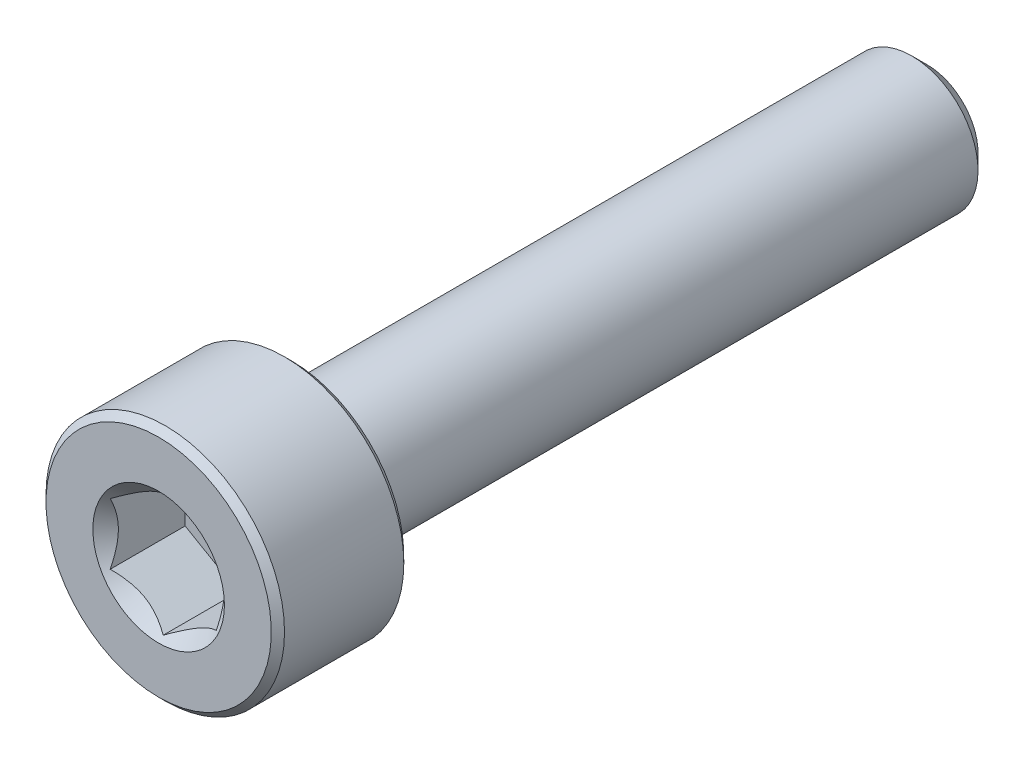
SolidWorks part; units mm, degrees
ref_plane "Front Plane" through (0, 0, 0) normal (0, 0, 1) x (1, 0, 0)
ref_plane "Top Plane" through (0, 0, 0) normal (0, 1, 0) x (1, 0, 0)
ref_plane "Right Plane" through (0, 0, 0) normal (1, 0, 0) x (0, 0, -1)
sketch "Sketch1" plane through (0, 0, 0) normal (1, 0, 0) x (0, 0, -1)
  line L0 (-7.25, 0) -> (7.25, 0) construction
  line L1 (7.25, 0) -> (7.25, 0.9577) construction
  line L2 (7.25, 0.9577) -> (6.9577, 1.25) construction
  line L3 (6.9577, 1.25) -> (6.9125, 1.25) construction
  line L4 (6.9125, 1.25) -> (-4.75, 1.25) construction
  line L5 (-4.75, 1.25) -> (-4.75, 2.25) construction
  line L6 (-4.75, 2.25) -> (-7.25, 2.25) construction
  line L7 (-7.25, 2.25) -> (-7.25, 0) construction
  line L8 (7.25, 0.9577) -> (7.25, 1.25) construction
  line L9 (7.2219, 1.2987) -> (7.4469, 0.909) construction
  line L10 (7.4469, 0.909) -> (7.6719, 1.2987) construction
  line L11 (7.6719, 1.2987) -> (7.2219, 1.2987) construction
  line L12 (7.4469, 1.2987) -> (7.4469, 1.25) construction
  line L13 (7.4469, 0.909) -> (7.4469, 0.9577) construction
  line L14 (7.4187, 0.9577) -> (7.475, 0.9577) construction
  line L15 (7.25, 1.25) -> (7.6438, 1.25) construction
  line L16 (7.2359, 1.2744) -> (7.6578, 1.2744) construction
  line L17 (7.25, 0) -> (7.25, -1.25) construction
  line L18 (-4.875, 2.25) -> (-4.75, 2.125) construction
  line L19 (-7.125, 2.25) -> (-7.25, 2.125) construction
  line L20 (-4.75, 1.25) -> (-4.75, 0) construction
  line L21 (-4.75, 0.625) -> (-0.75, 0.625) construction
  line L22 (-0.75, 0.625) -> (3.25, 0.625) construction
  line L23 (3.25, 0.625) -> (7.25, 0.625) construction
  line L24 (-0.75, 0.625) -> (-0.75, 1.25) construction
  line L25 (-0.75, 1.25) -> (-0.75, 2.25) construction
  line L26 (3.25, 0.625) -> (3.25, 2.25) construction
  point P0 (-7.25, 1)
  point P3 (6.125, 1.25)
  point P4 (0, 0)
  point P18 (3.25, 1.25)
  point P22 (7.4469, 0.9577)
  point P24 (6.9125, 1.25)
  point P25 (7.4469, 1.25)
  point P28 (7.4469, 1.2744)
  point P29 (6.125, -1.25)
  point P30 (-0.75, 1.25)
  point P31 (-6, 2.25)
  point P37 (-5.1875, 2.25)
  point P38 (-7.0625, 2.25)
  point P45 (-0.75, 0.625)
  point P46 (3.25, 0.625)
  dimension "D2" = 0.0563
  dimension "D7" = 0.125
  dimension "D8" = 0.125
  dimension "D9" = 0.125
  dimension "D10" = 0.0625
  dimension "D11" = 0.3125
  dimension "Drive Size" = 2
  dimension "Head Diameter" = 4.5
  dimension "Head Height" = 2.5
  dimension "Thread Pitch" = 0.45
  dimension "Thread Dia" = 2.5
  dimension "Length" = 12
  dimension "D12" = 0.3375
  dimension "D4" = 1.125
  dimension "D3" = 45
sketch "Sketch2" plane through (0, 0, 0) normal (1, 0, 0) x (0, 0, -1)
  line L0 (-7.25, 0) -> (-7.25, 2.125)
  line L1 (-7.125, 2.25) -> (-4.875, 2.25)
  line L2 (-4.75, 2.125) -> (-4.75, 1.375)
  line L4 (6.9577, 1.25) -> (7.25, 0.9577)
  line L5 (7.25, 0.9577) -> (7.25, 0)
  line L6 (-4.75, 2.25) -> (-7.25, 2.25) construction
  line L7 (7.25, 0) -> (-7.25, 0)
  line L8 (-7.125, 2.25) -> (-7.25, 2.125) construction
  line L10 (-7.125, 2.25) -> (-7.25, 2.125)
  line L14 (-4.875, 2.25) -> (-4.75, 2.125) construction
  line L16 (-4.875, 2.25) -> (-4.75, 2.125)
  line L17 (-4.75, 1.25) -> (-4.75, 2.25) construction
  line L19 (-4.625, 1.25) -> (6.9577, 1.25)
  line L20 (6.9125, 1.25) -> (-4.75, 1.25) construction
  arc A1 (-4.75, 1.375) -> (-4.625, 1.25) centre (-4.625, 1.375) ccw
  dimension "D3" = 0.125
revolve "Revolve1" add sketch "Sketch2" angle 360 about L7
sketch "Sketch3" plane through (0, 0, 7.25) normal (0, 0, 1) x (1, 0, 0)
  line L1 (1, -0.5774) -> (1, 0.5774)
  line L2 (1, 0.5774) -> (0, 1.1547)
  line L3 (0, 1.1547) -> (-1, 0.5774)
  line L4 (-1, 0.5774) -> (-1, -0.5774)
  line L5 (-1, -0.5774) -> (0, -1.1547)
  line L6 (0, -1.1547) -> (1, -0.5774)
  circle A0 centre (0, 0) radius 1 construction
  circle A1 centre (0, 0) radius 2.25 construction
  circle A2 centre (0, 0) radius 2.25 construction
  circle A3 centre (0, 0) radius 1.1547 construction
  point P13 (0, 0)
  dimension "D1" = 2.3094
extrude "Cut-Extrude1" cut sketch "Sketch3" against normal offset from surface (1.5 mm away) 1 up to face at (0, 2.125, 4.75)
sketch "Sketch4" plane through (0, 0, 7.25) normal (0, 0, 1) x (1, 0, 0)
  circle A0 centre (0, 0) radius 1.2413
  dimension "D1" = 2.4826
extrude "Cut-Extrude2" cut sketch "Sketch4" against normal up to vertex (1.25 mm away) draft 45 up to point (0, 2.25, 6)
sketch "Sketch11" plane through (0, 0, 0) normal (1, 0, 0) x (0, 0, -1)
  line L0 (-7.25, 0) -> (7.25, 0) construction
  line L1 (-7.25, 0) -> (7.25, 0) construction
  line L2 (-2.5, 0) -> (-2.5, 1.25) construction
  line L3 (6.9125, 1.25) -> (-4.75, 1.25) construction
  line L4 (5, 0) -> (5, 1.25) construction
  line L6 (7.25, 0.9577) -> (7.25, 1.25) construction
  point P2 (-2.5, 0)
  point P3 (5, 0)
  dimension "D1" = 2.25
  dimension "D2" = 2.25
sketch "Sketch6" plane through (0, 0, -7.25) normal (0, 0, -1) x (-1, 0, 0)
  circle A0 centre (0, 0) radius 1.25
curve "Helix/Spiral1" pitch 0.45 height 12.45 turns 27.6667
sketch "Sketch10" plane through (0, 0, 0) normal (1, 0, 0) x (0, 0, -1)
  line L0 (-4.625, -2.25) -> (-4.625, 2.25)
  line L5 (-7.25, 0) -> (7.25, 0) construction
  line L6 (-4.625, 1.25) -> (-4.625, -1.25) construction
  point P3 (-4.625, 0)
split "Split1" trim tools "Sketch10" bodies to split 106 resulting bodies 114 115
sketch "Sketch8" plane through (0, 0, 0) normal (1, 0, 0) x (0, 0, -1)
  line L0 (-4.75, 0) -> (-4.75, 1.25)
  line L1 (-4.625, -1.25) -> (-4.625, 1.25) construction
  line L2 (-4.75, 1.25) -> (-4.625, 1.25)
  line L4 (-4.625, 1.25) -> (-3.9033, 0)
  line L5 (-3.9033, 0) -> (-4.75, 0)
  line L6 (6.9125, 1.25) -> (-4.75, 1.25) construction
  line L7 (-7.25, 0) -> (7.25, 0) construction
  dimension "D1" = 60
revolve "Revolve2" add sketch "Sketch8" angle 360 about L5
equation "\"D2@Sketch1\" = \"Thread Pitch@Sketch1\" / 8"
equation "\"D4@Helix/Spiral1\" = \"Thread Pitch@Sketch1\""
equation "\"D7@Sketch1\" = \"Head Height@Sketch1\" * .05"
equation "\"D8@Sketch1\"=\"D7@Sketch1\""
equation "\"D9@Sketch1\"=\"D7@Sketch1\""
equation "\"D10@Sketch1\"=\"D7@Sketch1\"/2"
equation "\"D11@Sketch1\"=\"D10@Sketch1\"*5"
equation "\"D4@Sketch1\"=\"Thread Pitch@Sketch1\"*2.5"
equation "\"D12@Sketch1\"=\"Thread Pitch@Sketch1\"*.75"
equation "\"D3@Helix/Spiral1\"=\"Length@Sketch1\"+\"Thread Pitch@Sketch1\""
equation "\"D3@Sketch2\"=\"Thread Dia@Sketch1\"*0.05"
equation "\"D1@Sketch11\"=\"Length@Sketch1\"*0.1875"
equation "\"D2@Sketch11\"=\"D1@Sketch11\""
equation "\"D1@Sketch4\"=\"D1@Sketch3\"*1.075"
